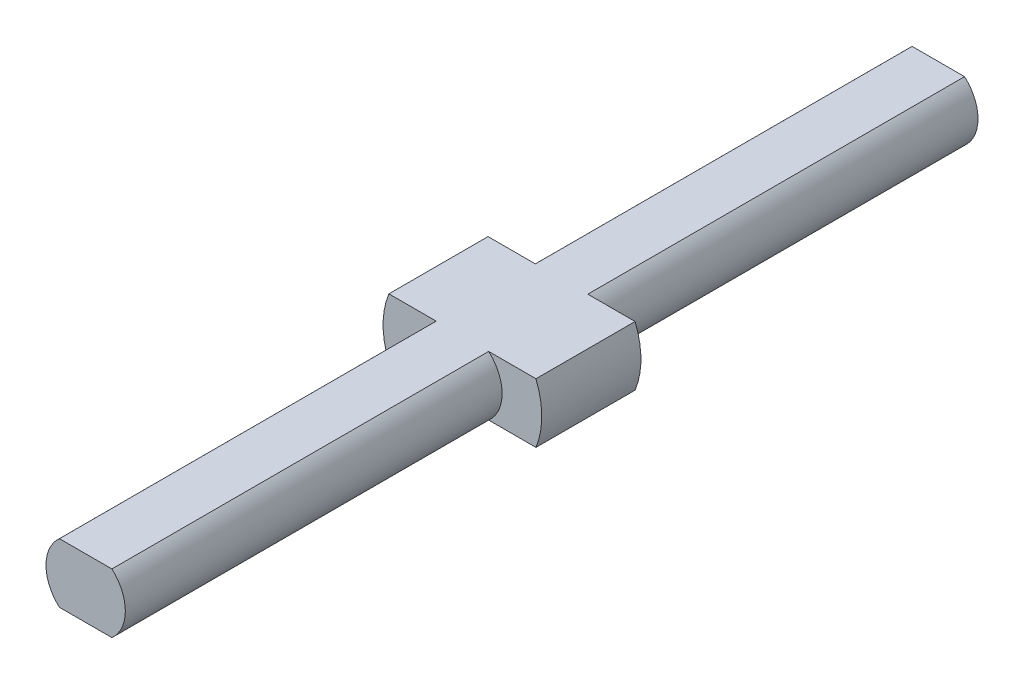
SolidWorks part; units mm, degrees
ref_plane "Front Plane" through (0, 0, 0) normal (0, 0, 1) x (1, 0, 0)
ref_plane "Top Plane" through (0, 0, 0) normal (0, 1, 0) x (1, 0, 0)
ref_plane "Right Plane" through (0, 0, 0) normal (1, 0, 0) x (0, 0, -1)
sketch "Sketch1" plane through (0, 0, 0) normal (0, 1, 0) x (1, 0, 0)
  line L0 (4, 43) -> (4, 5)
  line L1 (4, 5) -> (8, 5)
  line L2 (8, 5) -> (8, -5)
  line L3 (8, -5) -> (4, -5)
  line L4 (4, -5) -> (4, -43)
  line L5 (4, -43) -> (0, -43)
  line L6 (0, -43) -> (0, 43)
  line L7 (0, 43) -> (4, 43)
  line L8 (0, 0) -> (8, 0) construction
  dimension "D1" = 8
  dimension "D2" = 10
  dimension "D3" = 86
  dimension "D4" = 4
revolve "Revolve1" add sketch "Sketch1" angle 360 about L6
sketch "Sketch2" plane through (0, 0, 0) normal (0, 0, 1) x (1, 0, 0)
  line L0 (-8, 0) -> (0, 0) construction
  line L1 (-8, 8) -> (8, 8)
  line L2 (-8, 8) -> (-8, -8)
  line L3 (-8, -8) -> (8, -8)
  line L4 (8, 8) -> (8, -8)
  line L5 (-8, 3) -> (8, 3)
  line L6 (-8, 3) -> (-8, -3)
  line L7 (-8, -3) -> (8, -3)
  line L8 (8, 3) -> (8, -3)
  line L9 (0, 0) -> (8, 0) construction
  line L10 (0, 3) -> (0, 4) construction
  circle A0 centre (0, 0) radius 8 construction
  circle A1 centre (0, 0) radius 4 construction
  circle A2 centre (0, 0) radius 4 construction
  dimension "D1" = 1
extrude "Cut-Extrude1" cut sketch "Sketch2" against normal through all both and the other way through all contours L2 L5 L4 L1 | L7 L2 L3 L4
